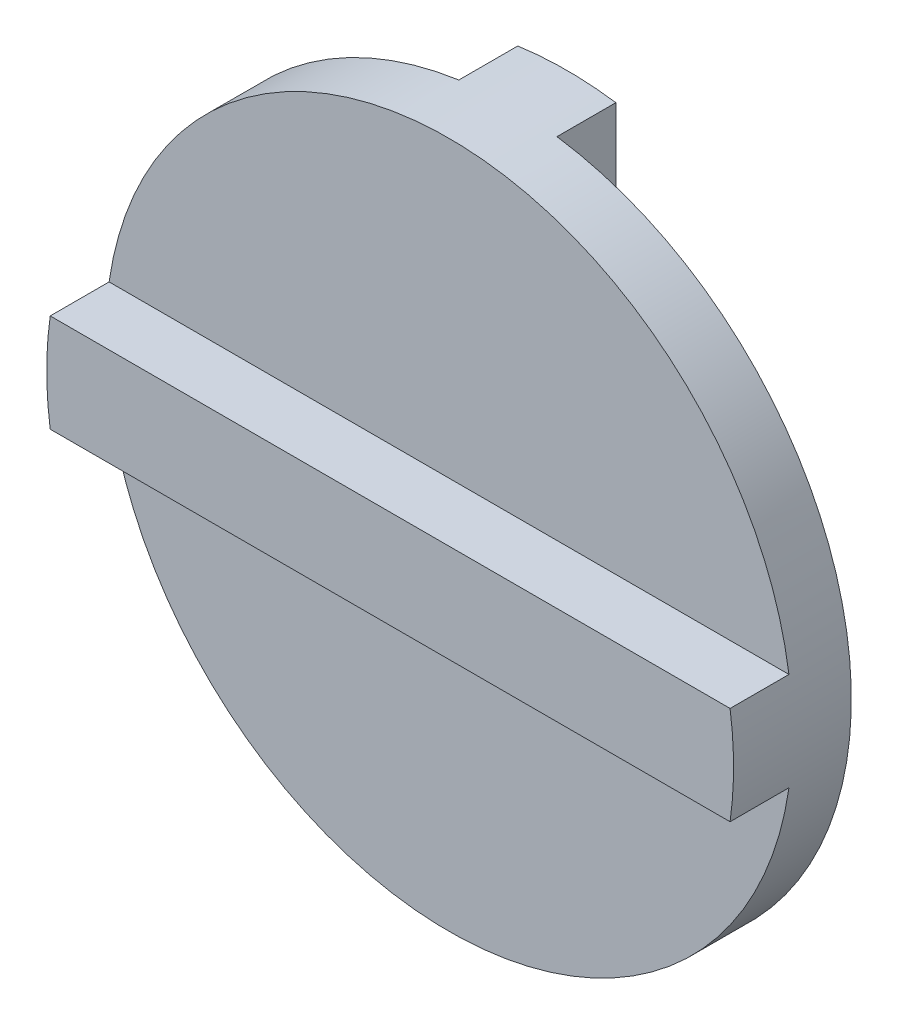
SolidWorks part; units mm, degrees
ref_plane "Front Plane" through (0, 0, 0) normal (0, 0, 1) x (1, 0, 0)
ref_plane "Top Plane" through (0, 0, 0) normal (0, 1, 0) x (1, 0, 0)
ref_plane "Right Plane" through (0, 0, 0) normal (1, 0, 0) x (0, 0, -1)
sketch "Sketch1" plane through (0, 0, 0) normal (0, 0, 1) x (1, 0, 0)
  circle A0 centre (0, 0) radius 35
  dimension "D1" = 70
extrude "Boss-Extrude1" add sketch "Sketch1" along normal mid plane 6
sketch "Sketch2" plane through (0, 0, 3) normal (0, 0, 1) x (1, 0, 0)
  line L1 (34.641, 5) -> (-34.641, 5)
  line L3 (34.641, -5) -> (-34.641, -5)
  line L5 (34.7694, 4.0114) -> (-34.7694, -4.0114) construction
  line L6 (34.7694, -4.0114) -> (-34.7694, 4.0114) construction
  circle A0 centre (0, 0) radius 35 construction
  arc A1 (-34.641, 5) -> (-34.641, -5) centre (0, 0) ccw
  arc A2 (34.641, -5) -> (34.641, 5) centre (0, 0) ccw
extrude "Boss-Extrude2" add sketch "Sketch2" along normal blind 6
sketch "Sketch3" plane through (0, 0, -3) normal (0, 0, -1) x (-1, 0, 0)
  line L2 (5, -34.641) -> (5, 34.641)
  line L4 (-5, -34.641) -> (-5, 34.641)
  line L5 (3.9501, -34.7764) -> (-3.9501, 34.7764) construction
  line L6 (3.9501, 34.7764) -> (-3.9501, -34.7764) construction
  circle A0 centre (0, 0) radius 35 construction
  arc A1 (-5, -34.641) -> (5, -34.641) centre (0, 0) ccw
  arc A2 (5, 34.641) -> (-5, 34.641) centre (0, 0) ccw
extrude "Boss-Extrude3" add sketch "Sketch3" along normal blind 6
